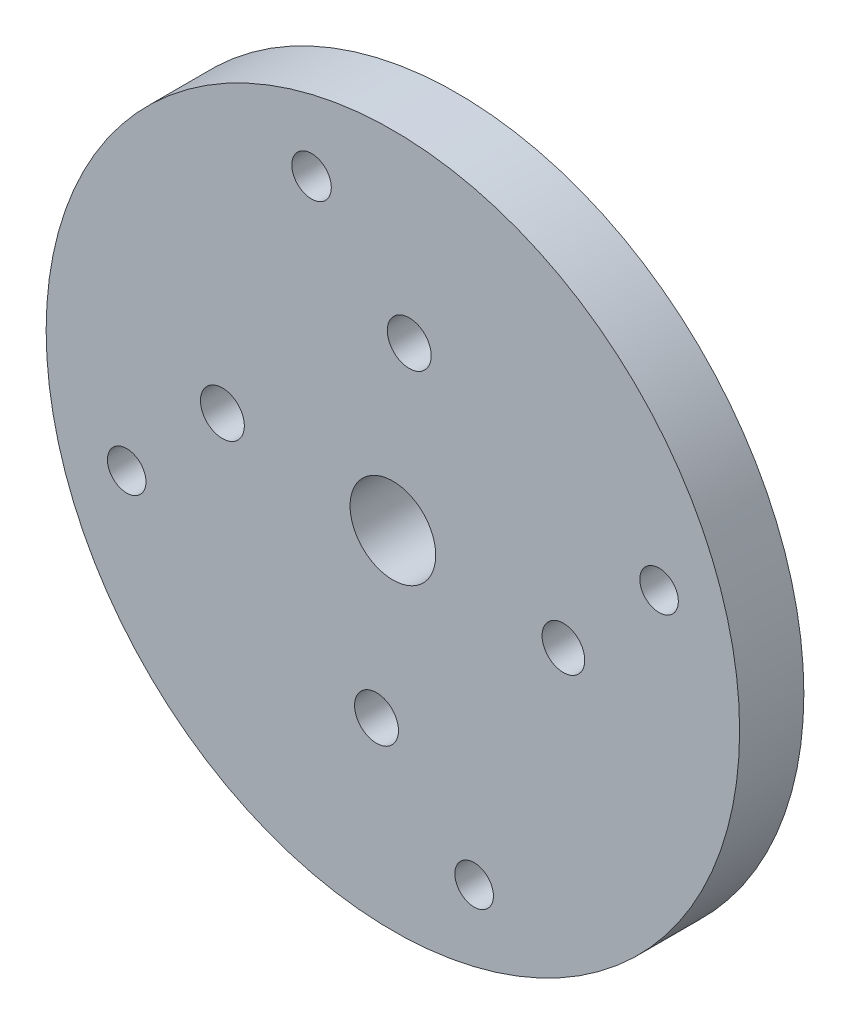
SolidWorks part; units mm, degrees
ref_plane "Plan de face" through (0, 0, 0) normal (0, 0, 1) x (1, 0, 0)
ref_plane "Plan de dessus" through (0, 0, 0) normal (0, 1, 0) x (1, 0, 0)
ref_plane "Plan de droite" through (0, 0, 0) normal (1, 0, 0) x (0, 0, -1)
sketch "Esquisse1" plane through (0, 0, 0) normal (0, 0, 1) x (1, 0, 0)
  circle A0 centre (0, 0) radius 16.1956
  circle A1 centre (0, 0) radius 2
extrude "Boss.-Extru.1" add sketch "Esquisse1" along normal blind 3
sketch "Esquisse3" plane through (0, 0, 3) normal (0, 0, 1) x (1, 0, 0)
  circle A0 centre (7.9634, -0.7647) radius 0.9976
  circle A1 centre (0.7647, 7.9634) radius 1.025
  circle A2 centre (-7.9634, 0.7647) radius 1.025
  circle A3 centre (-0.7647, -7.9634) radius 1.025
  circle A4 centre (-3.7994, 12.4324) radius 0.9229
  circle A5 centre (12.4324, 3.7994) radius 0.9
  circle A6 centre (3.7952, -12.4337) radius 0.9
  circle A7 centre (-12.4324, -3.7994) radius 0.9
extrude "Enlèv. mat.-Extru.2" cut sketch "Esquisse3" against normal through all
